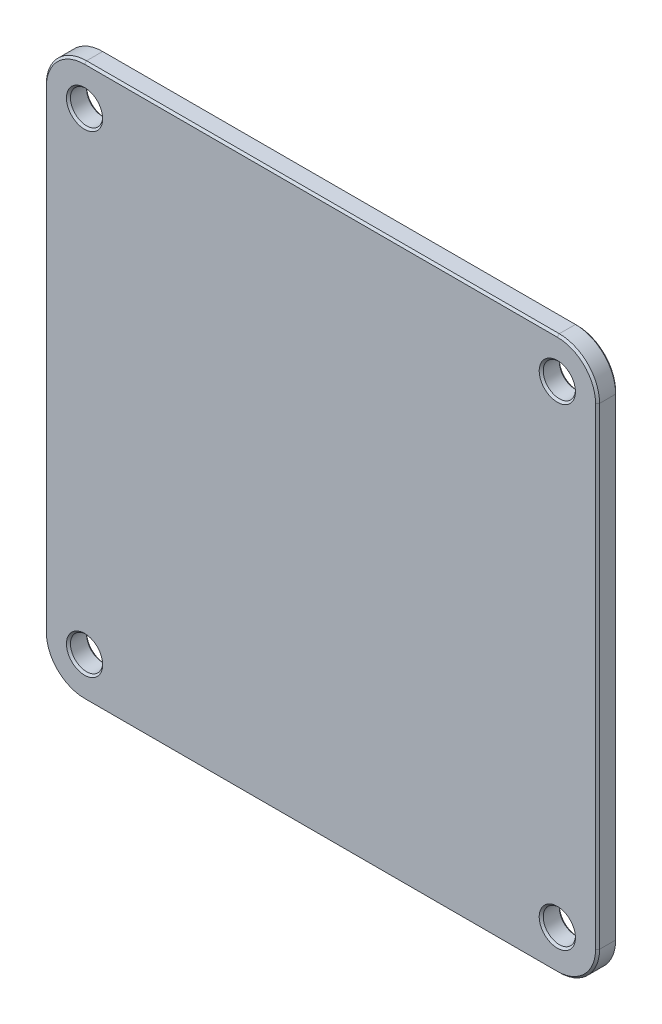
SolidWorks part; units mm, degrees
material "1060 Alloy"
ref_plane "Front Plane" through (0, 0, 0) normal (0, 0, 1) x (1, 0, 0)
ref_plane "Top Plane" through (0, 0, 0) normal (0, 1, 0) x (1, 0, 0)
ref_plane "Right Plane" through (0, 0, 0) normal (1, 0, 0) x (0, 0, -1)
sketch "Sketch3" plane through (0, 0, 0) normal (0, 0, 1) x (1, 0, 0)
  line L1 (-27.5, 27.5) -> (27.5, 27.5)
  line L2 (-27.5, 27.5) -> (-27.5, -27.5)
  line L3 (-27.5, -27.5) -> (27.5, -27.5)
  line L4 (27.5, 27.5) -> (27.5, -27.5)
  line L5 (0, -27.5) -> (0, 27.5) construction
  line L6 (-27.5, 0) -> (27.5, 0) construction
  point P0 (0, 0)
  dimension "D1" = 55
  dimension "D2" = 55
extrude "Boss-Extrude1" add sketch "Sketch3" along normal blind 2
sketch "Sketch4" plane through (0, 0, 2) normal (0, 0, 1) x (1, 0, 0)
  line L0 (27.5, 27.5) -> (-27.5, 27.5) construction
  line L1 (23.5, -23.5) -> (-23.5, -23.5) construction
  line L2 (23.5, -23.5) -> (23.5, 23.5) construction
  line L3 (23.5, 23.5) -> (-23.5, 23.5) construction
  line L4 (-23.5, -23.5) -> (-23.5, 23.5) construction
  line L5 (0, 23.5) -> (0, -23.5) construction
  line L6 (23.5, 0) -> (-23.5, 0) construction
  line L7 (27.5, -27.5) -> (27.5, 27.5) construction
  line L18 (-23.5, 27.5) -> (-27.5, 27.5)
  line L19 (-27.5, -23.5) -> (-27.5, -27.5) construction
  line L20 (23.5, -27.5) -> (27.5, -27.5) construction
  line L21 (27.5, 23.5) -> (27.5, 27.5) construction
  line L22 (27.5, -27.5) -> (27.5, 27.5)
  line L23 (-27.5, -27.5) -> (27.5, -27.5)
  line L24 (-27.5, 27.5) -> (-27.5, -27.5)
  line L25 (27.5, 27.5) -> (-27.5, 27.5)
  line L26 (27.5, -27.5) -> (27.5, -23.5) construction
  line L27 (-27.5, -27.5) -> (-23.5, -27.5) construction
  line L28 (-27.5, 27.5) -> (-27.5, 23.5)
  line L29 (27.5, 27.5) -> (23.5, 27.5) construction
  line L30 (23.5, 27.5) -> (27.5, 27.5)
  line L31 (27.5, 27.5) -> (27.5, 23.5)
  line L32 (27.5, -23.5) -> (27.5, -27.5)
  line L33 (27.5, -27.5) -> (23.5, -27.5)
  line L34 (-23.5, -27.5) -> (-27.5, -27.5)
  line L35 (-27.5, -27.5) -> (-27.5, -23.5)
  arc A0 (23.5, 27.5) -> (27.5, 23.5) centre (23.5, 23.5) cw
  arc A1 (-23.5, 27.5) -> (-27.5, 23.5) centre (-23.5, 23.5) ccw
  arc A2 (23.5, -27.5) -> (27.5, -23.5) centre (23.5, -23.5) ccw
  arc A3 (-23.5, -27.5) -> (-27.5, -23.5) centre (-23.5, -23.5) cw
  point P0 (0, 0)
  dimension "D1" = 47
  dimension "D2" = 47
  dimension "D3" = 0
extrude "Cut-Extrude1" cut sketch "Sketch4" against normal blind 2
sketch "Sketch6" plane through (0, 0, 2) normal (0, 0, 1) x (1, 0, 0)
  line L1 (23.5, -23.5) -> (-23.5, -23.5) construction
  line L2 (23.5, -23.5) -> (23.5, 23.5) construction
  line L3 (23.5, 23.5) -> (-23.5, 23.5) construction
  line L4 (-23.5, -23.5) -> (-23.5, 23.5) construction
  line L5 (0, 23.5) -> (0, -23.5) construction
  line L6 (23.5, 0) -> (-23.5, 0) construction
  circle A0 centre (23.5, 23.5) radius 1.6
  circle A1 centre (-23.5, 23.5) radius 1.6
  circle A2 centre (23.5, -23.5) radius 1.6
  circle A3 centre (-23.5, -23.5) radius 1.6
  point P0 (0, 0)
  dimension "D3" = 3.2
  dimension "D1" = 47
  dimension "D2" = 47
extrude "Cut-Extrude2" cut sketch "Sketch6" against normal through all
chamfer "Chamfer1" distance 0.2 angle 45 12 edges at (-26.3284, -26.3284, 0) (0, -27.5, 0) (26.3284, -26.3284, 0) (27.5, 0, 0) (26.3284, 26.3284, 0) (0, 27.5, 0) (-26.3284, 26.3284, 0) (-27.5, 0, 0) (25.1, 23.5, 0) (-21.9, -23.5, 0) (21.9, -23.5, 0) (-25.1, 23.5, 0)
chamfer "Chamfer2" distance 0.2 angle 45 12 edges at (0, 27.5, 2) (26.3284, 26.3284, 2) (27.5, 0, 2) (26.3284, -26.3284, 2) (0, -27.5, 2) (-26.3284, -26.3284, 2) (-27.5, 0, 2) (-26.3284, 26.3284, 2) (25.1, 23.5, 2) (-21.9, -23.5, 2) (21.9, -23.5, 2) (-25.1, 23.5, 2)
